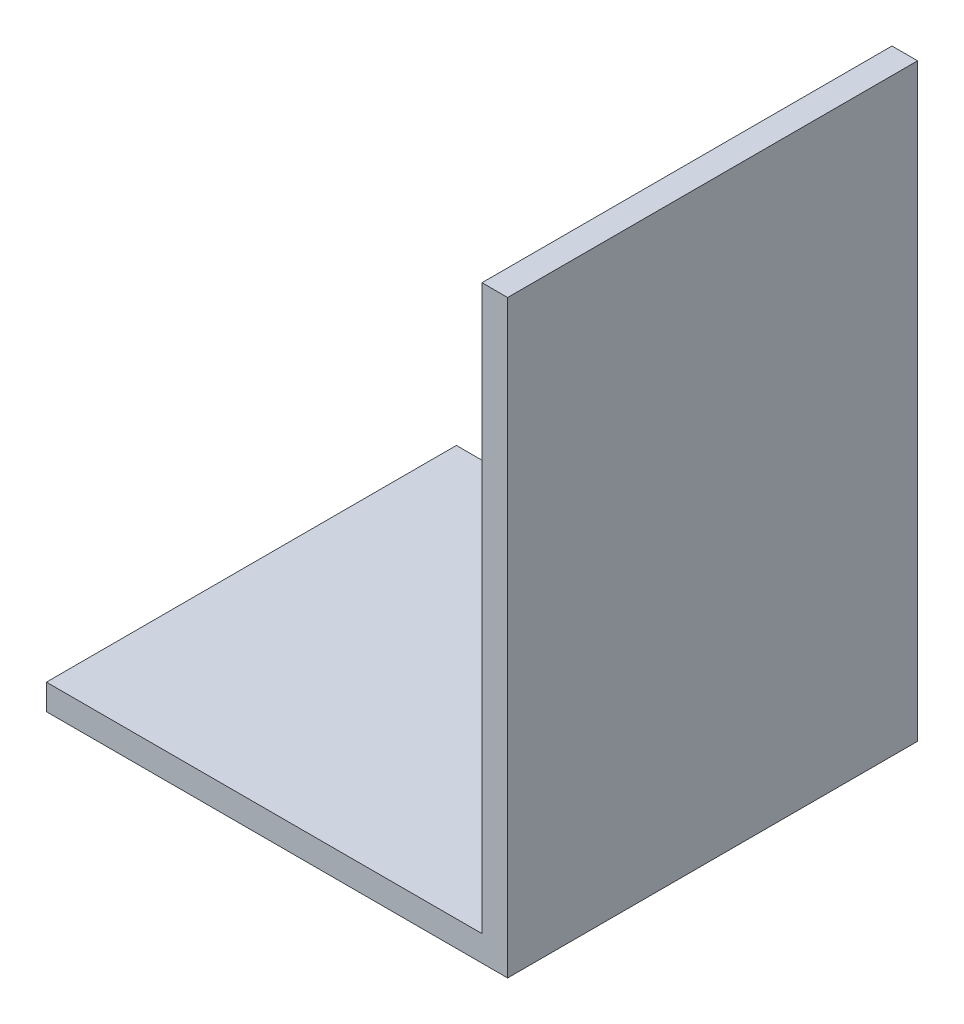
SolidWorks part; units mm, degrees
ref_plane "Front Plane" through (0, 0, 0) normal (0, 0, 1) x (1, 0, 0)
ref_plane "Top Plane" through (0, 0, 0) normal (0, 1, 0) x (1, 0, 0)
ref_plane "Right Plane" through (0, 0, 0) normal (1, 0, 0) x (0, 0, -1)
sketch "L angle load path profile" plane through (0, 0, 0) normal (0, 0, 1) x (1, 0, 0)
  line L0 (126, 7) -> (144, 7)
  line L1 (144, 7) -> (144, 30)
  line L2 (144, 30) -> (143, 30)
  line L3 (143, 30) -> (143, 8)
  line L4 (143, 8) -> (126, 8)
  line L5 (126, 8) -> (126, 7)
extrude "L angle load path" add sketch "L angle load path profile" along normal blind 16
